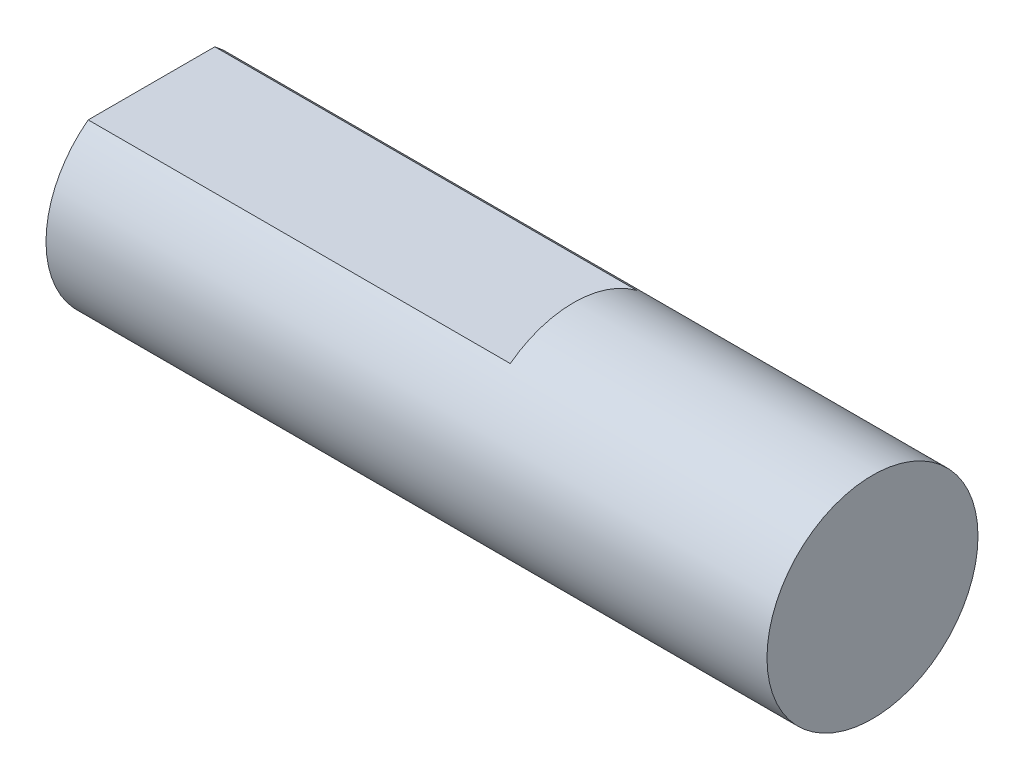
SolidWorks part; units mm, degrees
ref_plane "Front Plane" through (0, 0, 0) normal (0, 0, 1) x (1, 0, 0)
ref_plane "Top Plane" through (0, 0, 0) normal (0, 1, 0) x (1, 0, 0)
ref_plane "Right Plane" through (0, 0, 0) normal (1, 0, 0) x (0, 0, -1)
sketch "Sketch1" plane through (0, 0, 0) normal (0, 0, 1) x (1, 0, 0)
  line L0 (0, 0) -> (0, 3)
  line L1 (0, 3) -> (-20.5, 3)
  line L2 (-20.5, 3) -> (-20.5, 0)
  line L3 (-20.5, 0) -> (0, 0)
  dimension "D1" = 3
  dimension "D2" = 20.5
revolve "Revolve1" add sketch "Sketch1" angle 360 about L3
sketch "Sketch2" plane through (0, 0, 0) normal (0, 0, 1) x (1, 0, 0)
  line L0 (-20.5, 3) -> (-20.5, -3) construction
  line L1 (-20.5, 2.4) -> (-8.5, 2.4)
  line L2 (-20.5, 2.4) -> (-20.5, 4.4)
  line L3 (-20.5, 4.4) -> (-8.5, 4.4)
  line L4 (-8.5, 2.4) -> (-8.5, 4.4)
  line L5 (0, 3) -> (-20.5, 3) construction
  dimension "D1" = 2
  dimension "D2" = 0.6
  dimension "D3" = 12
extrude "Cut-Extrude1" cut sketch "Sketch2" against normal up to next and the other way up to next
